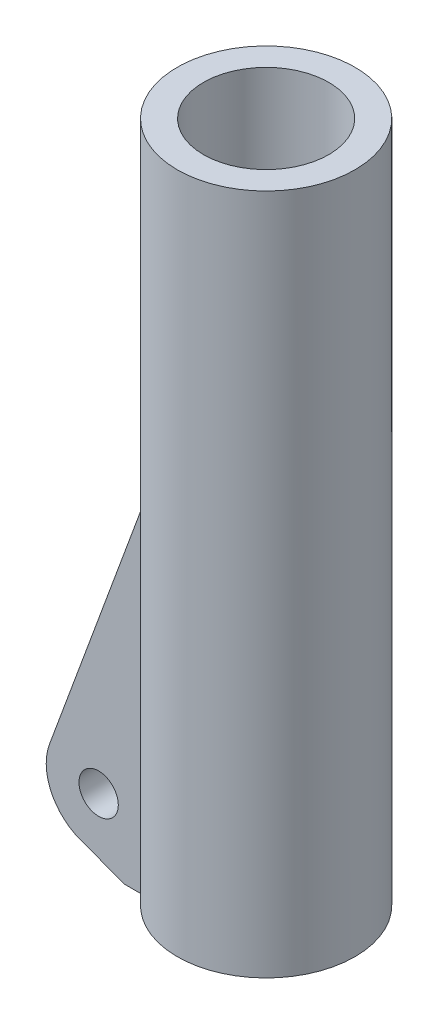
SolidWorks part; units mm, degrees
material "Choose your Material"
ref_plane "Front Plane" through (0, 0, 0) normal (0, 0, 1) x (1, 0, 0)
ref_plane "Top Plane" through (0, 0, 0) normal (0, 1, 0) x (1, 0, 0)
ref_plane "Right Plane" through (0, 0, 0) normal (1, 0, 0) x (0, 0, -1)
sketch "Sketch1" plane through (0, 0, 0) normal (0, 1, 0) x (1, 0, 0)
  circle A0 centre (0, 0) radius 30.353
  circle A1 centre (0, 0) radius 43.053
  dimension "D1" = 60.706
  dimension "D2" = 12.7
extrude "Boss-Extrude1" add sketch "Sketch1" along normal mid plane 330.2
sketch "Sketch2" plane through (0, 0, 0) normal (0, 0, 1) x (1, 0, 0)
  line L0 (-43.053, 165.1) -> (-43.053, -165.1) construction
  line L1 (-64.5359, -157.1832) -> (-43.053, -165.1)
  line L2 (-79.5862, -124.5671) -> (-30.353, 9.031)
  line L3 (-43.053, -165.1) -> (43.053, -165.1) construction
  line L4 (-43.053, -165.1) -> (-30.353, -165.1)
  line L5 (-30.353, -165.1) -> (-30.353, 9.031)
  arc A0 (-79.5862, -124.5671) -> (-64.5359, -157.1832) centre (-55.753, -133.35) ccw
  circle A1 centre (-55.753, -133.35) radius 9.525
  dimension "D2" = 50.8
  dimension "D4" = 19.05
  dimension "D1" = 12.7
  dimension "D3" = 31.75
  dimension "D5" = 12.7
extrude "Boss-Extrude2" add sketch "Sketch2" along normal mid plane 50.8
equation "\"diameter\"= 25.65"
equation "\"OleoDia\"=2.39"
equation "\"D1@Sketch1\"=\"OleoDia\""
equation "\"D1@Boss-Extrude1\"=13"
equation "\"D1@Boss-Extrude2\"=2"
